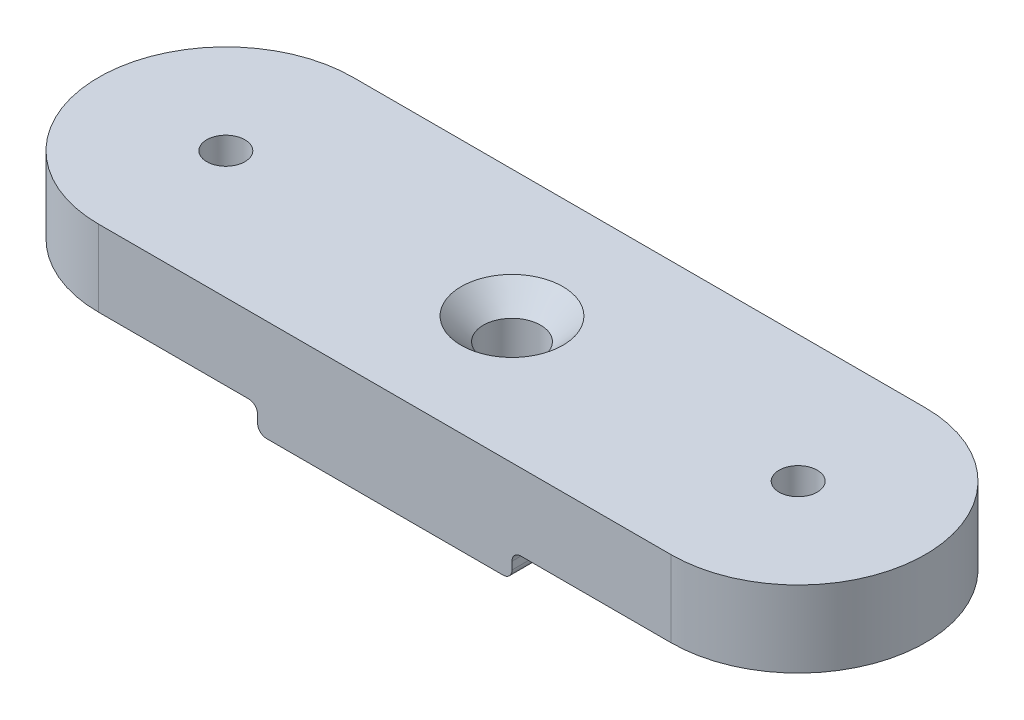
SolidWorks part; units mm, degrees
ref_plane "Front Plane" through (0, 0, 0) normal (0, 0, 1) x (1, 0, 0)
ref_plane "Top Plane" through (0, 0, 0) normal (0, 1, 0) x (1, 0, 0)
ref_plane "Right Plane" through (0, 0, 0) normal (1, 0, 0) x (0, 0, -1)
sketch "Sketch1" plane through (0, 0, 0) normal (0, 1, 0) x (1, 0, 0)
  line L0 (-22.5, 0) -> (22.5, 0) construction
  line L1 (-4.4, 0) -> (4.4, 0) construction
  line L2 (-22.5, 10) -> (22.5, 10)
  line L3 (-22.5, -10) -> (22.5, -10)
  line L4 (0, -4.4) -> (0, 4.4) construction
  arc A0 (-22.5, 10) -> (-22.5, -10) centre (-22.5, 0) ccw
  arc A1 (22.5, -10) -> (22.5, 10) centre (22.5, 0) ccw
  circle A2 centre (-22.5, 0) radius 1.5
  circle A3 centre (22.5, 0) radius 1.5
  circle A4 centre (0, 0) radius 2.25
  point P5 (0, 0)
  dimension "D1" = 3
  dimension "D2" = 3
  dimension "D5" = 4.5
  dimension "D3" = 20
  dimension "D4" = 45
extrude "Boss-Extrude1" add sketch "Sketch1" along normal blind 8
chamfer "Chamfer1" distance 1.75 angle 45 1 edges at (0, 8, 2.25)
sketch "Sketch3" plane through (0, 0, 0) normal (0, -1, 0) x (1, 0, 0)
  line L0 (-10, 10) -> (-22.5, 10)
  line L2 (-22.5, -10) -> (22.5, -10)
  line L3 (22.5, 10) -> (-22.5, 10)
  line L4 (-22.5, -10) -> (-10, -10)
  line L5 (22.5, 10) -> (10, 10)
  line L6 (-10, -10) -> (-10, 10)
  line L8 (10, -10) -> (10, 10)
  line L9 (10, -10) -> (22.5, -10)
  line L10 (-10, 10) -> (10, 10) construction
  line L11 (0, -4.4) -> (0, 4.4) construction
  arc A2 (-22.5, 10) -> (-22.5, -10) centre (-22.5, 0) ccw
  arc A3 (22.5, -10) -> (22.5, 10) centre (22.5, 0) ccw
  arc A4 (-22.5, 10) -> (-22.5, -10) centre (-22.5, 0) ccw
  arc A5 (22.5, -10) -> (22.5, 10) centre (22.5, 0) ccw
  point P10 (0, 10)
  dimension "D1" = 0
extrude "Cut-Extrude1" cut sketch "Sketch3" against normal offset from surface (2 mm away) 6 up to face at (0, 8, 4)
sketch "Sketch4" plane through (0, 2, 0) normal (0, -1, 0) x (1, 0, 0)
  circle A0 centre (-22.5, 0) radius 3
  circle A1 centre (22.5, 0) radius 3
  circle A2 centre (22.5, 0) radius 1.5 construction
  circle A3 centre (-22.5, 0) radius 1.5 construction
  dimension "D1" = 6
extrude "Cut-Extrude2" cut sketch "Sketch4" against normal blind 3
fillet "Fillet1" radius 0.7 4 edges at (10, 0, 0) (10, 2, 0) (-10, 0, 0) (-10, 2, 0)
fillet "Fillet2" radius 0.5 2 edges at (22.5, 2, -3) (-22.5, 2, -3)
